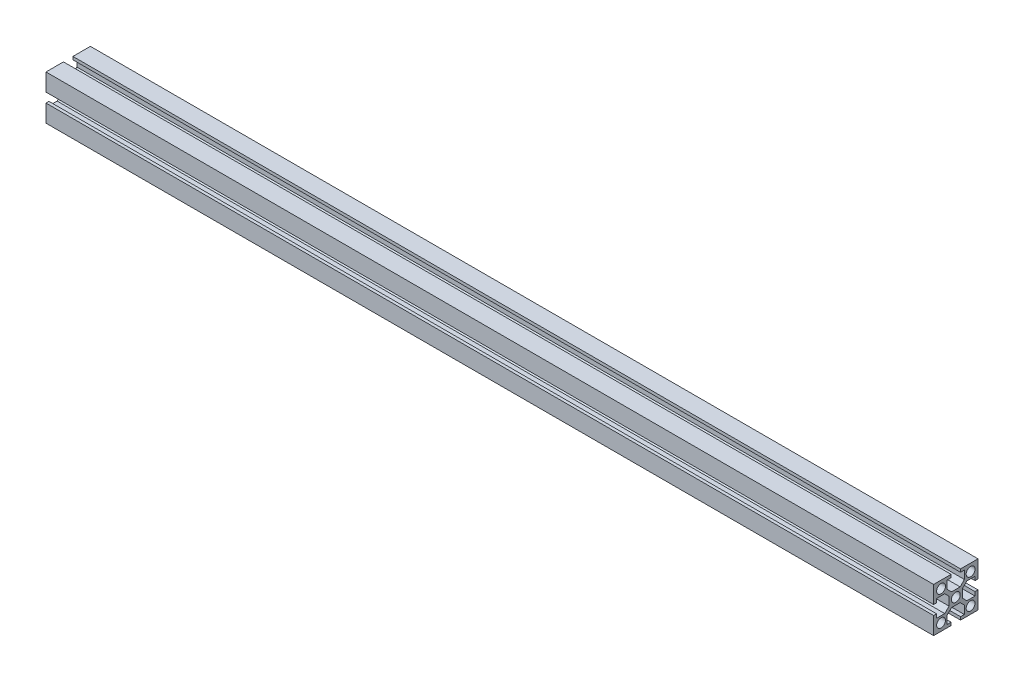
SolidWorks part; units mm, degrees
ref_plane "Front Plane" through (0, 0, 0) normal (0, 0, 1) x (1, 0, 0)
ref_plane "Top Plane" through (0, 0, 0) normal (0, 1, 0) x (1, 0, 0)
ref_plane "Right Plane" through (0, 0, 0) normal (1, 0, 0) x (0, 0, -1)
ref_plane "Plane1" through (-50, 0, 0) normal (-1, 0, 0) x (0, -1, 0)
sketch "Sketch1" plane through (-50, 0, 0) normal (-1, 0, 0) x (0, -1, 0)
  line L0 (5.2, -11.4515) -> (3.7515, -12.9)
  line L1 (3.7515, -12.9) -> (1, -12.9)
  line L2 (1, -12.9) -> (1, -11.6)
  line L3 (1, -11.6) -> (0, -11.6)
  line L4 (0, -11.6) -> (0, -17.5)
  line L5 (0, -17.5) -> (5.9, -17.5)
  line L6 (5.9, -17.5) -> (5.9, -16.5)
  line L7 (5.9, -16.5) -> (4.6, -16.5)
  line L8 (4.6, -16.5) -> (4.6, -13.7485)
  line L9 (4.6, -13.7485) -> (6.0485, -12.3)
  line L10 (6.0485, -12.3) -> (8.9515, -12.3)
  line L11 (8.9515, -12.3) -> (10.4, -13.7485)
  line L12 (10.4, -13.7485) -> (10.4, -16.5)
  line L13 (10.4, -16.5) -> (9.1, -16.5)
  line L14 (9.1, -16.5) -> (9.1, -17.5)
  line L15 (9.1, -17.5) -> (15, -17.5)
  line L16 (15, -17.5) -> (15, -11.6)
  line L17 (15, -11.6) -> (14, -11.6)
  line L18 (14, -11.6) -> (14, -12.9)
  line L19 (14, -12.9) -> (11.2485, -12.9)
  line L20 (11.2485, -12.9) -> (9.8, -11.4515)
  line L21 (9.8, -11.4515) -> (9.8, -8.5485)
  line L22 (9.8, -8.5485) -> (11.2485, -7.1)
  line L23 (11.2485, -7.1) -> (14, -7.1)
  line L24 (14, -7.1) -> (14, -8.4)
  line L25 (14, -8.4) -> (15, -8.4)
  line L26 (15, -8.4) -> (15, -2.5)
  line L27 (15, -2.5) -> (9.1, -2.5)
  line L28 (9.1, -2.5) -> (9.1, -3.5)
  line L29 (9.1, -3.5) -> (10.4, -3.5)
  line L30 (10.4, -3.5) -> (10.4, -6.2515)
  line L31 (10.4, -6.2515) -> (8.9515, -7.7)
  line L32 (8.9515, -7.7) -> (6.0485, -7.7)
  line L33 (6.0485, -7.7) -> (4.6, -6.2515)
  line L34 (4.6, -6.2515) -> (4.6, -3.5)
  line L35 (4.6, -3.5) -> (5.9, -3.5)
  line L36 (5.9, -3.5) -> (5.9, -2.5)
  line L37 (5.9, -2.5) -> (0, -2.5)
  line L38 (0, -2.5) -> (0, -8.4)
  line L39 (0, -8.4) -> (1, -8.4)
  line L40 (1, -8.4) -> (1, -7.1)
  line L41 (1, -7.1) -> (3.7515, -7.1)
  line L42 (3.7515, -7.1) -> (5.2, -8.5485)
  line L43 (5.2, -8.5485) -> (5.2, -11.4515)
  circle A0 centre (7.5, -10) radius 1.5
  circle A1 centre (2.5, -5) radius 1.5
  circle A2 centre (2.5, -15) radius 1.5
  circle A3 centre (12.5, -5) radius 1.5
  circle A4 centre (12.5, -15) radius 1.5
extrude "Boss-Extrude1" add sketch "Sketch1" against normal blind 300
